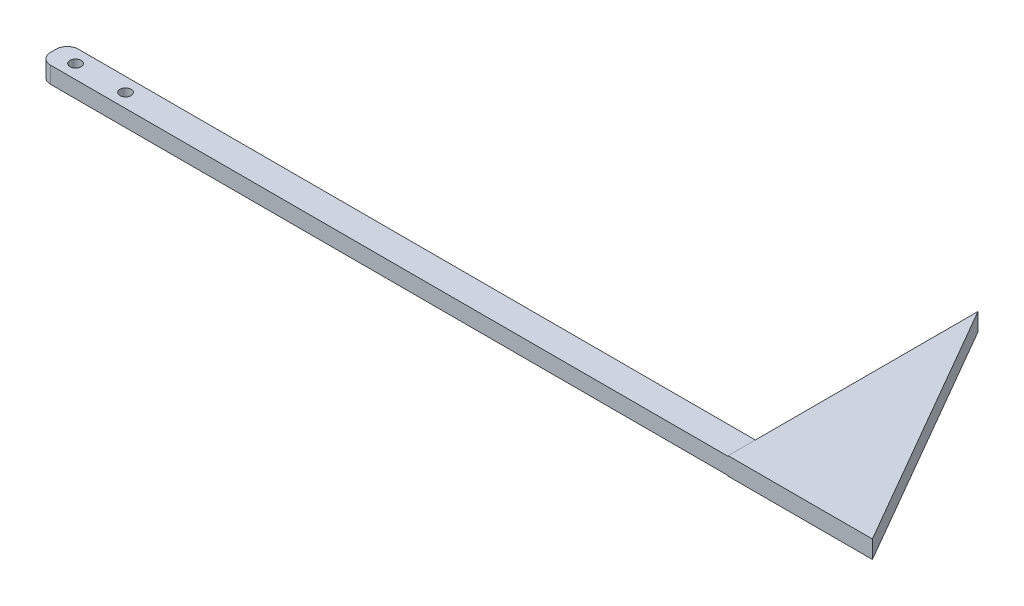
SolidWorks part; units mm, degrees
material "PET"
ref_plane "Front Plane" through (0, 0, 0) normal (0, 0, 1) x (1, 0, 0)
ref_plane "Top Plane" through (0, 0, 0) normal (0, 1, 0) x (1, 0, 0)
ref_plane "Right Plane" through (0, 0, 0) normal (1, 0, 0) x (0, 0, -1)
sketch "Sketch1" plane through (0, 0, 0) normal (0, 1, 0) x (1, 0, 0)
  line L0 (0, 0) -> (150, 0)
  line L2 (124.0192, 5) -> (0, 5)
  line L3 (0, 5) -> (0, 0)
  line L6 (124.0192, 5) -> (124.0192, 45)
  line L7 (124.0192, 45) -> (150, 0)
  circle A0 centre (4, 2.5) radius 1
  circle A1 centre (13, 2.5) radius 1
  point P10 (0, 0)
  dimension "D5" = 2
  dimension "D6" = 2
  dimension "D1" = 150
  dimension "D2" = 5
  dimension "D3" = 40
  dimension "D4" = 60
  dimension "D7" = 9
  dimension "D8" = 4
  dimension "D9" = 2.5
extrude "Boss-Extrude1" add sketch "Sketch1" along normal blind 3
fillet "Fillet1" radius 2 2 edges at (0, 1.5, 0) (0, 1.5, -5)
sketch "Sketch2" plane through (0, 3, 0) normal (0, 1, 0) x (1, 0, 0)
  line L0 (150, 0) -> (124.0192, 45)
  line L1 (124.0192, 45) -> (124.0192, 0)
  line L2 (2, 0) -> (150, 0) construction
  line L3 (124.0192, 0) -> (150, 0)
extrude "Boss-Extrude2" add sketch "Sketch2" along normal blind 0.1
sketch "Sketch3" plane through (0, 0, 0) normal (0, -1, 0) x (1, 0, 0)
  line L0 (124.0192, -45) -> (150, 0)
  line L1 (124.0192, -45) -> (124.0192, 0)
  line L2 (124.0192, 0) -> (150, 0)
extrude "Boss-Extrude3" add sketch "Sketch3" along normal blind 0.1
